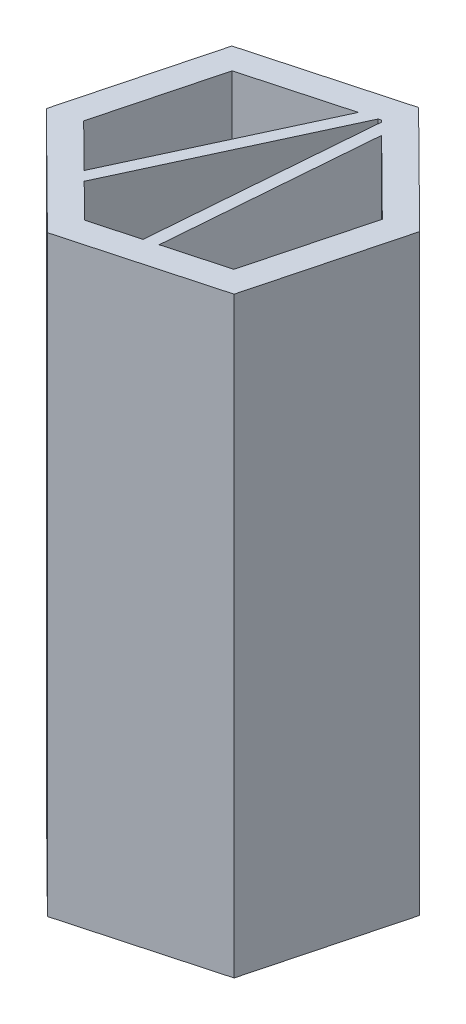
SolidWorks part; units mm, degrees
ref_plane "Front Plane" through (0, 0, 0) normal (0, 0, 1) x (1, 0, 0)
ref_plane "Top Plane" through (0, 0, 0) normal (0, 1, 0) x (1, 0, 0)
ref_plane "Right Plane" through (0, 0, 0) normal (1, 0, 0) x (0, 0, -1)
sketch "Sketch1" plane through (0, 0, 0) normal (0, 1, 0) x (1, 0, 0)
  line L1 (8.2059, -8.1238) -> (11.1384, 3.0446)
  line L2 (11.1384, 3.0446) -> (2.9325, 11.1684)
  line L3 (2.9325, 11.1684) -> (-8.2059, 8.1238)
  line L4 (-8.2059, 8.1238) -> (-11.1384, -3.0446)
  line L5 (-11.1384, -3.0446) -> (-2.9325, -11.1684)
  line L6 (-2.9325, -11.1684) -> (8.2059, -8.1238)
  line L7 (-2.346, -8.9347) -> (6.5647, -6.4991)
  line L8 (6.5647, -6.4991) -> (8.9107, 2.4357)
  line L9 (8.9107, 2.4357) -> (2.346, 8.9347)
  line L10 (2.346, 8.9347) -> (-6.5647, 6.4991)
  line L11 (-6.5647, 6.4991) -> (-8.9107, -2.4357)
  line L12 (-8.9107, -2.4357) -> (-2.346, -8.9347)
  circle A0 centre (0, 0) radius 10 construction
  circle A1 centre (0, 0) radius 8 construction
  dimension "D1" = 20
  dimension "D2" = 2
extrude "Boss-Extrude1" add sketch "Sketch1" along normal blind 45
sketch "Sketch2" plane through (0, 45, 0) normal (0, 1, 0) x (1, 0, 0)
  line L0 (-5.6284, -5.6852) -> (0.9665, 8.5577)
  line L1 (-8.9107, -2.4357) -> (-2.346, -8.9347) construction
  line L2 (2.346, 8.9347) -> (-6.5647, 6.4991) construction
  line L3 (0.9665, 8.5577) -> (2.1531, 8.882)
  line L4 (2.1531, 8.882) -> (-4.9177, -6.3888)
  line L5 (-4.9177, -6.3888) -> (-5.6284, -5.6852)
  line L6 (2.1094, -7.7169) -> (3.3623, 7.9286)
  line L7 (-2.346, -8.9347) -> (6.5647, -6.4991) construction
  line L8 (8.9107, 2.4357) -> (2.346, 8.9347) construction
  line L9 (3.3623, 7.9286) -> (2.4881, 8.794)
  line L10 (2.4881, 8.794) -> (1.1447, -7.9806)
  line L11 (1.1447, -7.9806) -> (2.1094, -7.7169)
  dimension "D1" = 0.2
  dimension "D2" = 0.2
  dimension "D3" = 1
  dimension "D4" = 1
extrude "Boss-Extrude2" add sketch "Sketch2" against normal blind 45
